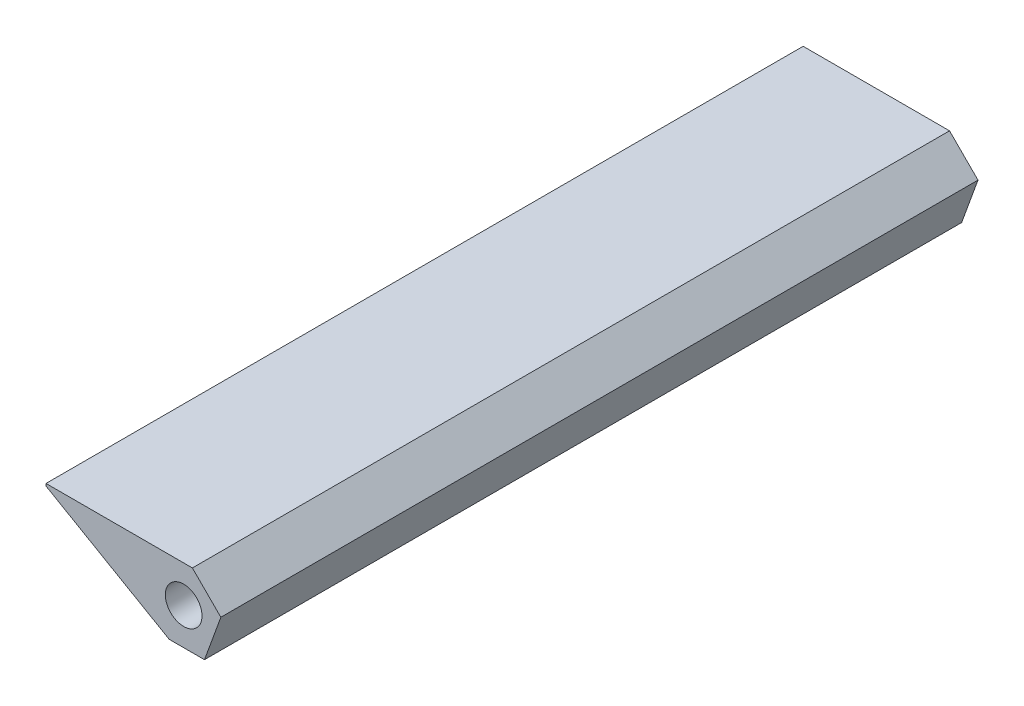
SolidWorks part; units mm, degrees
material "PE1000 hellgrau"
ref_plane "Vorne" through (0, 0, 0) normal (0, 0, 1) x (1, 0, 0)
ref_plane "Oben" through (0, 0, 0) normal (0, 1, 0) x (1, 0, 0)
ref_plane "Rechts" through (0, 0, 0) normal (1, 0, 0) x (0, 0, -1)
sketch "Skizze1" plane through (0, 0, 0) normal (0, 0, 1) x (1, 0, 0)
  line L0 (-30, 8) -> (1.8995, 8)
  line L1 (8.1031, 1.7964) -> (4.5375, -8)
  line L2 (4.5375, -8) -> (-3.1532, -8)
  line L3 (-3.1532, -8) -> (-30, 7.5)
  line L4 (-30, 7.5) -> (-30, 8)
  line L5 (1.8995, 8) -> (8.1031, 1.7964)
  circle A0 centre (0, 0) radius 4
  dimension "D1" = 8
  dimension "D2" = 8
  dimension "D3" = 30
  dimension "D4" = 0.5
  dimension "D5" = 16
  dimension "D6" = 45
  dimension "D7" = 245
  dimension "D8" = 7
  dimension "D9" = 7
  dimension "D10" = 30
extrude "Aufsatz-Linear austragen1" add sketch "Skizze1" along normal mid plane 165
